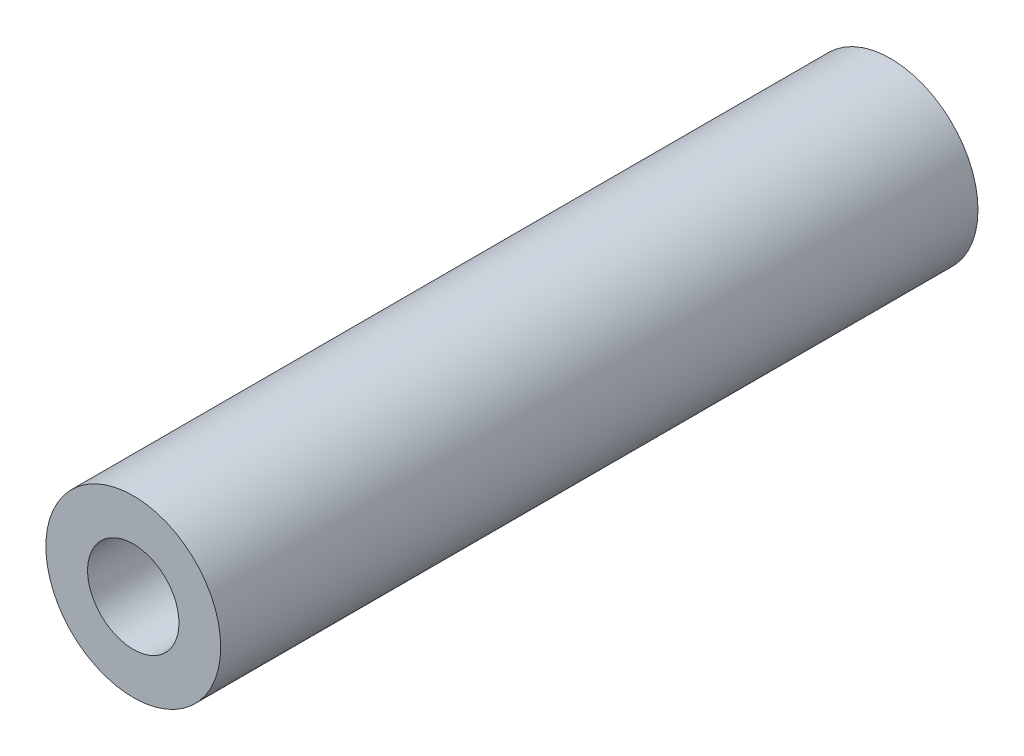
SolidWorks part; units mm, degrees
ref_plane "Front Plane" through (0, 0, 0) normal (0, 0, 1) x (1, 0, 0)
ref_plane "Top Plane" through (0, 0, 0) normal (0, 1, 0) x (1, 0, 0)
ref_plane "Right Plane" through (0, 0, 0) normal (1, 0, 0) x (0, 0, -1)
sketch "Sketch1" plane through (0, 0, 0) normal (0, 0, 1) x (1, 0, 0)
  circle A0 centre (0, 0) radius 2.4892
  circle A1 centre (0, 0) radius 4.7625
  dimension "D1" = 4.9784
  dimension "D2" = 9.525
extrude "Boss-Extrude1" add sketch "Sketch1" along normal mid plane 41.2496
